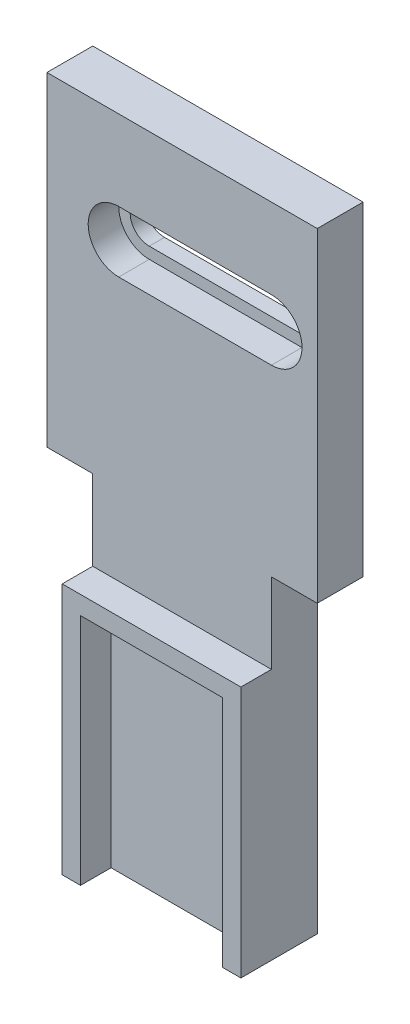
SolidWorks part; units mm, degrees
ref_plane "Front Plane" through (0, 0, 0) normal (0, 0, 1) x (1, 0, 0)
ref_plane "Top Plane" through (0, 0, 0) normal (0, 1, 0) x (1, 0, 0)
ref_plane "Right Plane" through (0, 0, 0) normal (1, 0, 0) x (0, 0, -1)
sketch "Sketch1" plane through (0, 0, 0) normal (0, 0, 1) x (1, 0, 0)
  line L1 (-43.4143, 34.026) -> (-25.7143, 34.026)
  line L2 (-43.4143, 34.026) -> (-43.4143, -8.974)
  line L3 (-43.4143, -8.974) -> (-25.7143, -8.974)
  line L4 (-25.7143, 34.026) -> (-25.7143, -8.974)
  dimension "D1" = 17.7
  dimension "D2" = 43
extrude "Boss-Extrude1" add sketch "Sketch1" along normal blind 3
sketch "Sketch2" plane through (0, 0, 3) normal (0, 0, 1) x (1, 0, 0)
  line L1 (-43.4143, -8.974) -> (-40.4143, -8.974)
  line L2 (-43.4143, -8.974) -> (-43.4143, 12.776)
  line L3 (-43.4143, 12.776) -> (-40.4143, 12.776)
  line L4 (-40.4143, -8.974) -> (-40.4143, 12.776)
  line L5 (-25.7143, -8.974) -> (-28.7143, -8.974)
  line L6 (-25.7143, -8.974) -> (-25.7143, 12.776)
  line L7 (-25.7143, 12.776) -> (-28.7143, 12.776)
  line L8 (-28.7143, -8.974) -> (-28.7143, 12.776)
  dimension "D1" = 21.75
  dimension "D2" = 21.75
  dimension "D3" = 3
  dimension "D4" = 3
extrude "Cut-Extrude1" cut sketch "Sketch2" against normal through all
sketch "Sketch3" plane through (0, 0, 3) normal (0, 0, 1) x (1, 0, 0)
  line L0 (-28.7143, 26.776) -> (-38.7143, 26.776) construction
  line L1 (-28.7143, 25.526) -> (-38.7143, 25.526)
  line L2 (-28.7143, 28.026) -> (-38.7143, 28.026)
  line L3 (-25.7143, 34.026) -> (-43.4143, 34.026) construction
  line L4 (-25.7143, 12.776) -> (-25.7143, 34.026) construction
  arc A0 (-28.7143, 25.526) -> (-28.7143, 28.026) centre (-28.7143, 26.776) ccw
  arc A1 (-38.7143, 28.026) -> (-38.7143, 25.526) centre (-38.7143, 26.776) ccw
  point P2 (-33.7143, 26.776)
  dimension "D3" = 3
  dimension "D1" = 6
  dimension "D2" = 2.5
  dimension "D4" = 10
extrude "Cut-Extrude2" cut sketch "Sketch3" against normal through all
sketch "Sketch4" plane through (0, 0, 3) normal (0, 0, 1) x (1, 0, 0)
  line L0 (-38.7143, 26.776) -> (-28.7143, 26.776) construction
  line L1 (-38.7143, 28.776) -> (-28.7143, 28.776)
  line L2 (-38.7143, 24.776) -> (-28.7143, 24.776)
  arc A0 (-38.7143, 28.776) -> (-38.7143, 24.776) centre (-38.7143, 26.776) ccw
  arc A1 (-28.7143, 24.776) -> (-28.7143, 28.776) centre (-28.7143, 26.776) ccw
  point P4 (-33.7143, 26.776)
  dimension "D1" = 4
extrude "Cut-Extrude3" cut sketch "Sketch4" against normal blind 2
sketch "Sketch5" plane through (0, 0, 3) normal (0, 0, 1) x (1, 0, 0)
  line L0 (-28.7143, 12.776) -> (-28.7143, -8.974) construction
  line L1 (-40.4143, -8.974) -> (-28.7143, -8.974)
  line L2 (-40.4143, -8.974) -> (-40.4143, 7.526)
  line L3 (-40.4143, 7.526) -> (-28.7143, 7.526)
  line L4 (-28.7143, -8.974) -> (-28.7143, 7.526)
  dimension "D1" = 16.5
extrude "Boss-Extrude2" add sketch "Sketch5" along normal blind 2
sketch "Sketch6" plane through (0, 0, 5) normal (0, 0, 1) x (1, 0, 0)
  line L0 (-40.4143, -8.974) -> (-28.7143, -8.974) construction
  line L1 (-39.2143, -8.974) -> (-29.9143, -8.974)
  line L2 (-39.2143, -8.974) -> (-39.2143, 6.326)
  line L3 (-39.2143, 6.326) -> (-29.9143, 6.326)
  line L4 (-29.9143, -8.974) -> (-29.9143, 6.326)
  line L5 (-40.4143, 7.526) -> (-40.4143, -8.974) construction
  line L6 (-28.7143, -8.974) -> (-28.7143, 7.526) construction
  line L7 (-28.7143, 7.526) -> (-40.4143, 7.526) construction
  dimension "D1" = 1.2
  dimension "D2" = 1.2
  dimension "D3" = 1.2
extrude "Cut-Extrude4" cut sketch "Sketch6" against normal blind 2
